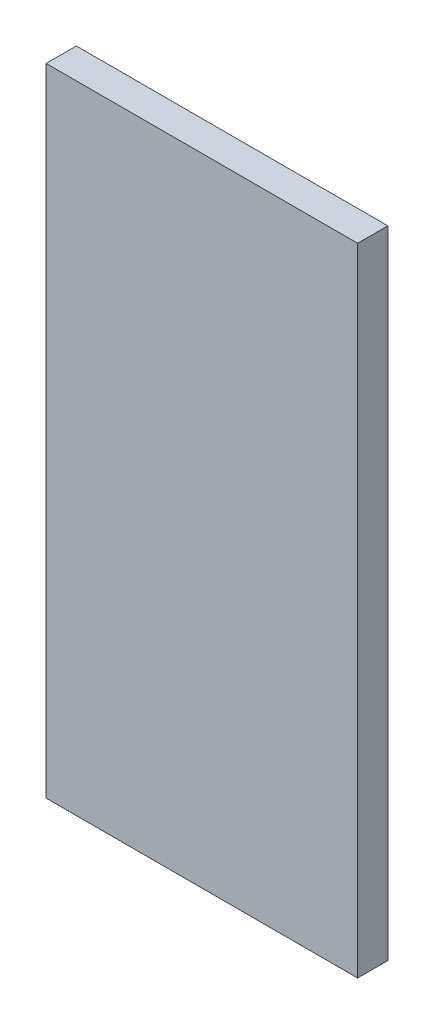
SolidWorks part; units mm, degrees
ref_plane "Front Plane" through (0, 0, 0) normal (0, 0, 1) x (1, 0, 0)
ref_plane "Top Plane" through (0, 0, 0) normal (0, 1, 0) x (1, 0, 0)
ref_plane "Right Plane" through (0, 0, 0) normal (1, 0, 0) x (0, 0, -1)
sketch "Sketch1" plane through (0, 0, 0) normal (0, 0, 1) x (1, 0, 0)
  line L0 (0, 0) -> (490, 0)
  line L1 (0, 0) -> (0, 1001)
  line L2 (490, 0) -> (490, 1001)
  line L3 (0, 1001) -> (490, 1001)
  dimension "D1" = 1001
  dimension "D2" = 490
extrude "Boss-Extrude1" add sketch "Sketch1" along normal blind 47.5
